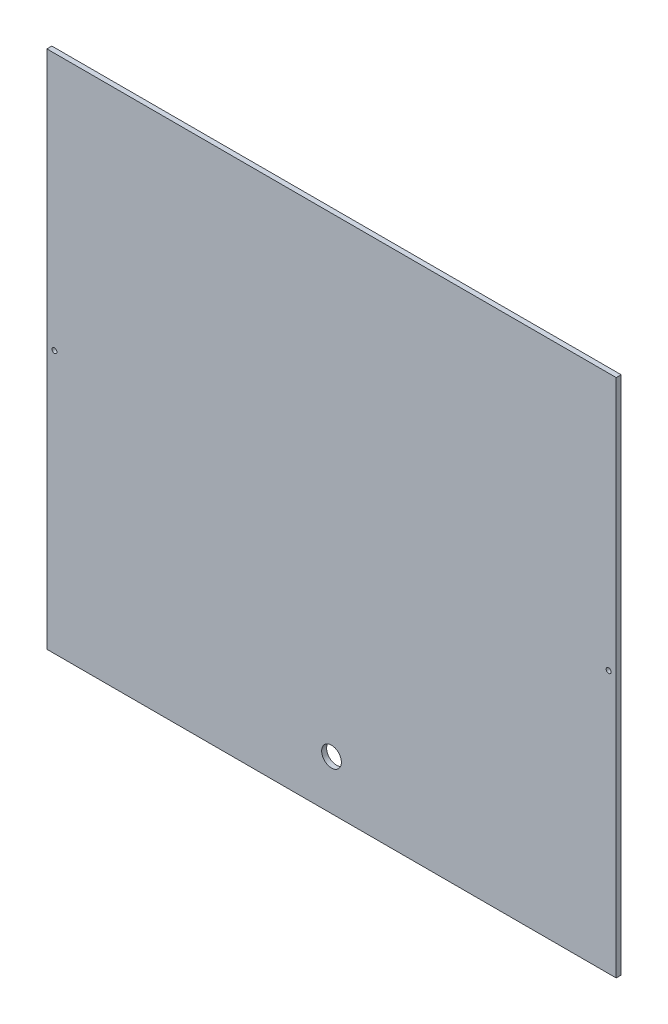
SolidWorks part; units mm, degrees
ref_plane "Front Plane" through (0, 0, 0) normal (0, 0, 1) x (1, 0, 0)
ref_plane "Top Plane" through (0, 0, 0) normal (0, 1, 0) x (1, 0, 0)
ref_plane "Right Plane" through (0, 0, 0) normal (1, 0, 0) x (0, 0, -1)
sketch "Sketch1" plane through (0, 0, 0) normal (0, 0, 1) x (1, 0, 0)
  line L0 (0, 263.3488) -> (25, 263.3488) construction
  line L1 (0, 0) -> (576.6976, 0)
  line L2 (0, 0) -> (0, 526.6976)
  line L3 (0, 526.6976) -> (576.6976, 526.6976)
  line L4 (576.6976, 0) -> (576.6976, 526.6976)
  line L5 (288.3488, 526.6976) -> (288.3488, 458.4329) construction
  circle A2 centre (7.6442, 265.8488) radius 2.5
  circle A3 centre (569.0534, 265.8488) radius 2.5
extrude "Boss-Extrude1" add sketch "Sketch1" along normal blind 5
sketch "Sketch2" plane through (0, 0, 0) normal (0, 0, -1) x (-1, 0, 0)
  line L0 (-288.3488, 0) -> (-288.3488, 50) construction
  circle A0 centre (-288.3488, 50) radius 10
extrude "Cut-Extrude1" cut sketch "Sketch2" against normal blind 10
